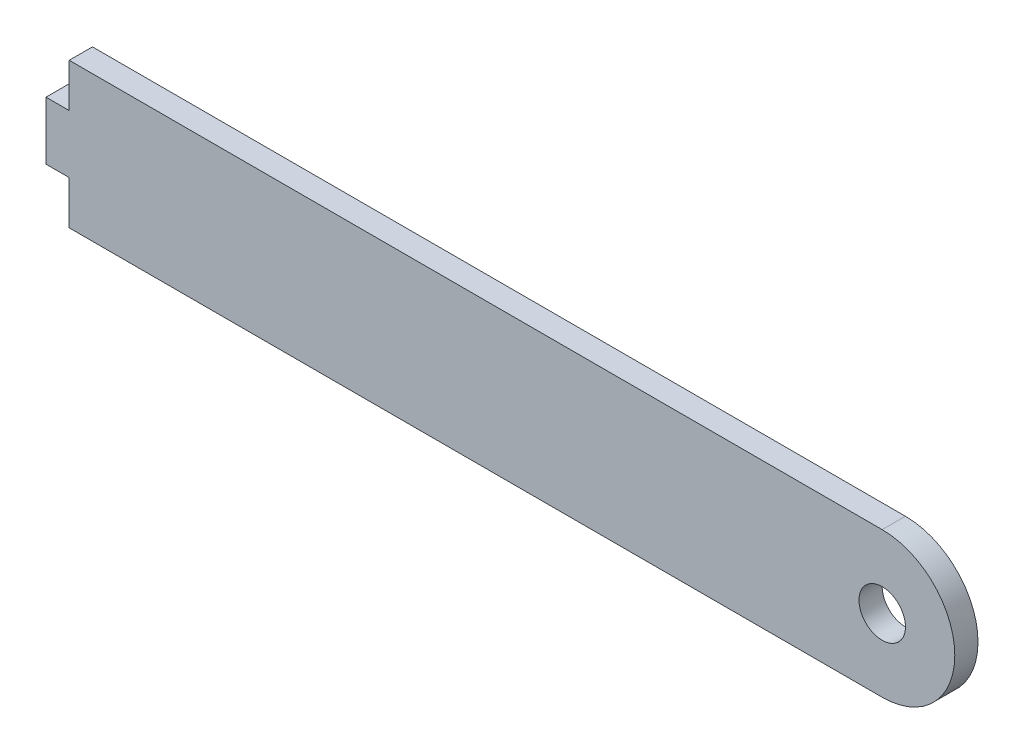
SolidWorks part; units mm, degrees
material "Oak"
ref_plane "Front Plane" through (0, 0, 0) normal (0, 0, 1) x (1, 0, 0)
ref_plane "Top Plane" through (0, 0, 0) normal (0, 1, 0) x (1, 0, 0)
ref_plane "Right Plane" through (0, 0, 0) normal (1, 0, 0) x (0, 0, -1)
sketch "Sketch2" plane through (0, 0, 0) normal (0, 0, 1) x (1, 0, 0)
  line L0 (-48.2028, -6.4616) -> (-48.2028, -13.9616)
  line L1 (-48.2028, 11.0384) -> (91.7972, 11.0384)
  line L2 (-48.2028, -13.9616) -> (91.7972, -13.9616)
  line L4 (-48.2028, 11.0384) -> (-48.2028, 3.5384)
  line L5 (-48.2028, -6.4616) -> (-52.2028, -6.4616)
  line L7 (-48.2028, 3.5384) -> (-52.2028, 3.5384)
  line L8 (-52.2028, -6.4616) -> (-52.2028, 3.5384)
  arc A1 (91.7972, -13.9616) -> (91.7972, 11.0384) centre (91.7972, -1.4616) ccw
  circle A3 centre (91.7972, -1.4616) radius 4
  point P0 (-48.2028, -1.4616)
  point P3 (15.1732, 0)
  dimension "D3" = 8
  dimension "D4" = 12.5
  dimension "D2" = 140
  dimension "D5" = 10
extrude "Boss-Extrude1" add sketch "Sketch2" along normal blind 4
